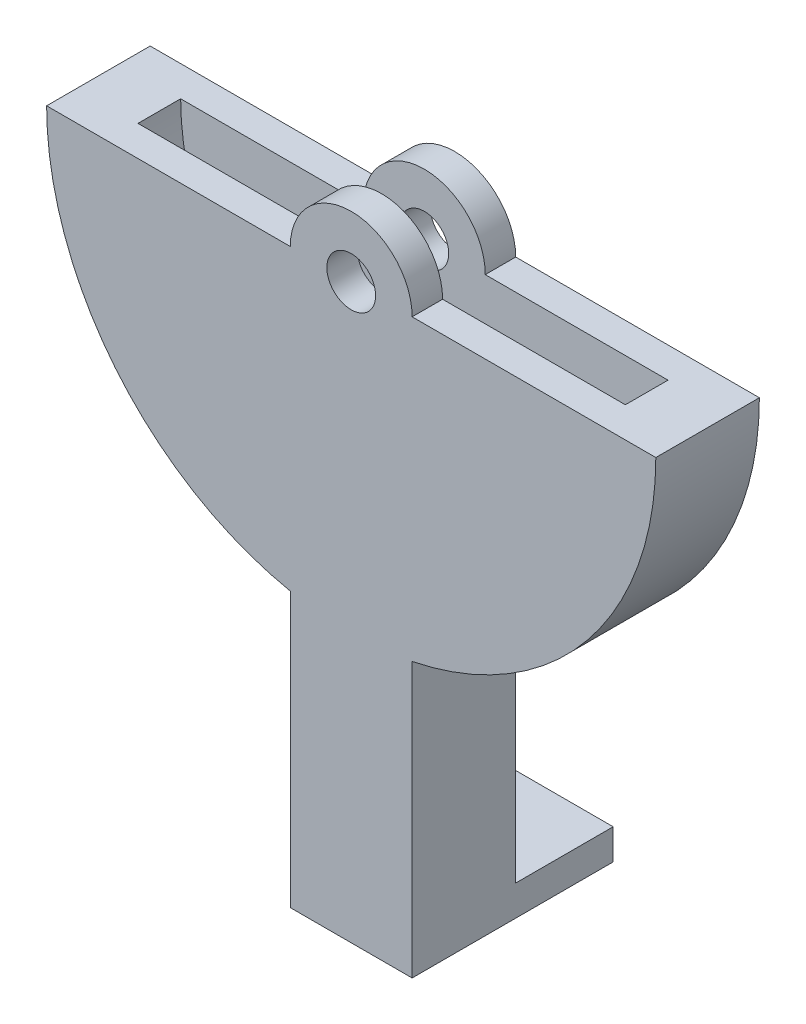
SolidWorks part; units mm, degrees
ref_plane "Front Plane" through (0, 0, 0) normal (0, 0, 1) x (1, 0, 0)
ref_plane "Top Plane" through (0, 0, 0) normal (0, 1, 0) x (1, 0, 0)
ref_plane "Right Plane" through (0, 0, 0) normal (1, 0, 0) x (0, 0, -1)
sketch "Sketch1" plane through (0, 0, 0) normal (0, 0, 1) x (1, 0, 0)
  line L0 (-50, 0) -> (-10, 0)
  line L1 (10, 0) -> (50, 0)
  arc A0 (-50, 0) -> (50, 0) centre (0, 0) ccw
  circle A1 centre (0, 0) radius 4
  arc A2 (10, 0) -> (-10, 0) centre (0, 0) ccw
extrude "Boss-Extrude1" add sketch "Sketch1" along normal blind 5
sketch "Sketch2" plane through (0, 0, 5) normal (0, 0, 1) x (1, 0, 0)
  line L0 (-50, 0) -> (-40, 0)
  line L1 (40, 0) -> (50, 0)
  arc A0 (-50, 0) -> (50, 0) centre (0, 0) ccw
  arc A1 (-40, 0) -> (40, 0) centre (0, 0) ccw
extrude "Boss-Extrude2" add sketch "Sketch2" along normal blind 7
sketch "Sketch3" plane through (0, 0, 12) normal (0, 0, 1) x (1, 0, 0)
  line L0 (-50, 0) -> (-10, 0)
  line L1 (10, 0) -> (50, 0)
  arc A0 (-50, 0) -> (50, 0) centre (0, 0) ccw
  arc A1 (10, 0) -> (-10, 0) centre (0, 0) ccw
  circle A2 centre (0, 0) radius 4
extrude "Boss-Extrude3" add sketch "Sketch3" along normal blind 5
sketch "Sketch4" plane through (0, 0, 17) normal (0, 0, 1) x (1, 0, 0)
  line L0 (10, -88.9898) -> (-10, -88.9898)
  line L1 (10, -88.9898) -> (10, -48.9898)
  line L2 (-10, -88.9898) -> (-10, -48.9898)
  arc A4 (-50, 0) -> (50, 0) centre (0, 0) ccw construction
  dimension "D2" = 20
  dimension "D3" = 40
extrude "Boss-Extrude4" add sketch "Sketch4" against normal blind 17
sketch "Sketch5" plane through (0, -88.9898, 0) normal (0, -1, 0) x (1, 0, 0)
  line L1 (-10, 17) -> (10, 17)
  line L2 (-10, 17) -> (-10, -16)
  line L3 (-10, -16) -> (10, -16)
  line L4 (10, 17) -> (10, -16)
  dimension "D1" = 33
extrude "Boss-Extrude5" add sketch "Sketch5" along normal blind 5
